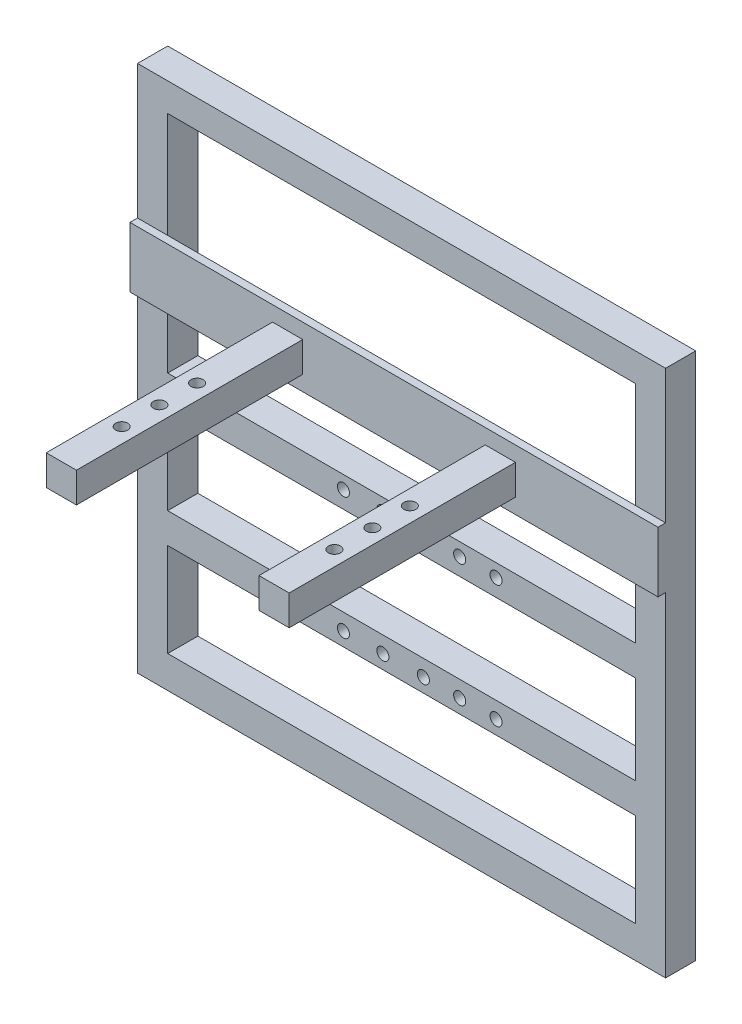
SolidWorks part; units mm, degrees
ref_plane "Front Plane" through (0, 0, 0) normal (0, 0, 1) x (1, 0, 0)
ref_plane "Top Plane" through (0, 0, 0) normal (0, 1, 0) x (1, 0, 0)
ref_plane "Right Plane" through (0, 0, 0) normal (1, 0, 0) x (0, 0, -1)
sketch "Sketch1" plane through (0, 0, 0) normal (0, 0, 1) x (1, 0, 0)
  line L0 (-155.3766, -157.955) -> (154.6234, -157.955)
  line L1 (-175.3766, 88.785) -> (174.6234, 88.785)
  line L2 (-175.3766, 88.785) -> (-175.3766, -261.215)
  line L3 (-175.3766, -261.215) -> (174.6234, -261.215)
  line L4 (174.6234, 88.785) -> (174.6234, -261.215)
  line L5 (-155.3766, 70.045) -> (154.6234, 70.045)
  line L6 (-155.3766, 70.045) -> (-155.3766, -78.955)
  line L7 (-155.3766, -239.955) -> (154.6234, -239.955)
  line L8 (154.6234, 70.045) -> (154.6234, -78.955)
  line L9 (154.6234, -177.955) -> (-155.3766, -177.955)
  line L10 (-155.3766, -98.955) -> (-155.3766, -157.955)
  line L11 (-155.3766, -78.955) -> (154.6234, -78.955)
  line L13 (-155.3766, -98.955) -> (154.6234, -98.955)
  line L15 (154.6234, -98.955) -> (154.6234, -157.955)
  line L16 (154.6234, -177.955) -> (154.6234, -239.955)
  line L17 (-155.3766, -177.955) -> (-155.3766, -239.955)
  dimension "D1" = 350
  dimension "D2" = 350
  dimension "D3" = 310
  dimension "D4" = 310
  dimension "D5" = 20
  dimension "D6" = 62
  dimension "D7" = 20
  dimension "D8" = 59
  dimension "D9" = 20
extrude "Boss-Extrude1" add sketch "Sketch1" along normal blind 20
sketch "Sketch2" plane through (0, 0, 20) normal (0, 0, 1) x (1, 0, 0)
  line L0 (-175.3766, 88.785) -> (-175.3766, -261.215) construction
  line L1 (-175.3766, 0.045) -> (174.6234, 0.045)
  line L2 (-175.3766, 0.045) -> (-175.3766, -39.955)
  line L3 (-175.3766, -39.955) -> (174.6234, -39.955)
  line L4 (174.6234, 0.045) -> (174.6234, -39.955)
  line L5 (174.6234, -261.215) -> (174.6234, 88.785) construction
  line L6 (-155.3766, -78.955) -> (154.6234, -78.955) construction
  dimension "D1" = 40
  dimension "D2" = 39
extrude "Boss-Extrude2" add sketch "Sketch2" along normal blind 5
sketch "Sketch3" plane through (0, 0, 25) normal (0, 0, 1) x (1, 0, 0)
  line L0 (-175.3766, -39.955) -> (174.6234, -39.955) construction
  line L9 (-80.8766, -9.955) -> (-60.8766, -9.955)
  line L10 (-80.8766, -9.955) -> (-80.8766, -29.955)
  line L11 (-80.8766, -29.955) -> (-60.8766, -29.955)
  line L12 (-60.8766, -9.955) -> (-60.8766, -29.955)
  line L13 (60.1234, -9.955) -> (80.1234, -9.955)
  line L14 (60.1234, -9.955) -> (60.1234, -29.955)
  line L15 (60.1234, -29.955) -> (80.1234, -29.955)
  line L16 (80.1234, -9.955) -> (80.1234, -29.955)
  point P14 (-60.8766, -19.955)
  point P18 (-165.542, -8.455)
  point P19 (-165.542, -31.455)
  point P20 (164.458, -31.455)
  point P21 (164.458, -8.455)
  dimension "D1" = 20
  dimension "D2" = 20
  dimension "D3" = 20
  dimension "D4" = 20
  dimension "D5" = 121
  dimension "D6" = 10
  dimension "D7" = 10
extrude "Boss-Extrude4" add sketch "Sketch3" along normal blind 150
sketch "Sketch4" plane through (0, -29.955, 0) normal (0, -1, 0) x (1, 0, 0)
  line L0 (-60.8766, 175) -> (-60.8766, 25) construction
  line L3 (-80.8766, 25) -> (-60.8766, 25)
  line L5 (-80.8766, 25) -> (-60.8766, 25) construction
  circle A0 centre (-70.8766, 135) radius 4
  circle A1 centre (-70.8766, 85) radius 4
  circle A2 centre (70.1234, 135) radius 4
  circle A3 centre (70.1234, 85) radius 4
  point P15 (-70.8766, 135)
  point P16 (-70.8766, 85)
  point P33 (70.1234, 135)
  point P34 (70.1234, 85)
  dimension "D3" = 8
  dimension "D1" = 50
extrude "Cut-Extrude1" cut sketch "Sketch4" against normal through all contours A3 | A2 | A0 | A1
sketch "Sketch5" plane through (0, 0, 20) normal (0, 0, 1) x (1, 0, 0)
  circle A0 centre (-38.9184, -87.5914) radius 4
  circle A1 centre (-12.765, -87.5914) radius 4
  circle A2 centre (14.0766, -87.5914) radius 4
  circle A3 centre (38.1653, -87.5914) radius 4
  circle A4 centre (62.2539, -87.5914) radius 4
  circle A5 centre (62.2539, -168.8046) radius 4
  circle A6 centre (38.1653, -168.8046) radius 4
  circle A7 centre (14.0766, -168.8046) radius 4
  circle A8 centre (-12.765, -168.8046) radius 4
  circle A9 centre (-38.9184, -168.8046) radius 4
  point P0 (-12.765, -87.5914)
  point P1 (14.0766, -87.5914)
  point P2 (38.1653, -87.5914)
  point P3 (62.2539, -87.5914)
  point P4 (-38.9184, -87.5914)
  point P5 (-38.9184, -168.8046)
  point P6 (-12.765, -168.8046)
  point P7 (14.0766, -168.8046)
  point P8 (38.1653, -168.8046)
  point P9 (62.2539, -168.8046)
  dimension "D1" = 8
extrude "Cut-Extrude2" cut sketch "Sketch5" against normal through all
sketch "Sketch6" plane through (0, -29.955, 0) normal (0, -1, 0) x (1, 0, 0)
  circle A0 centre (-70.8766, 110) radius 4
  circle A1 centre (70.2854, 110) radius 4
  point P4 (-70.8766, 110)
  point P5 (70.2854, 110)
  dimension "D1" = 8
  dimension "D2" = 8
extrude "Cut-Extrude3" cut sketch "Sketch6" against normal through all
